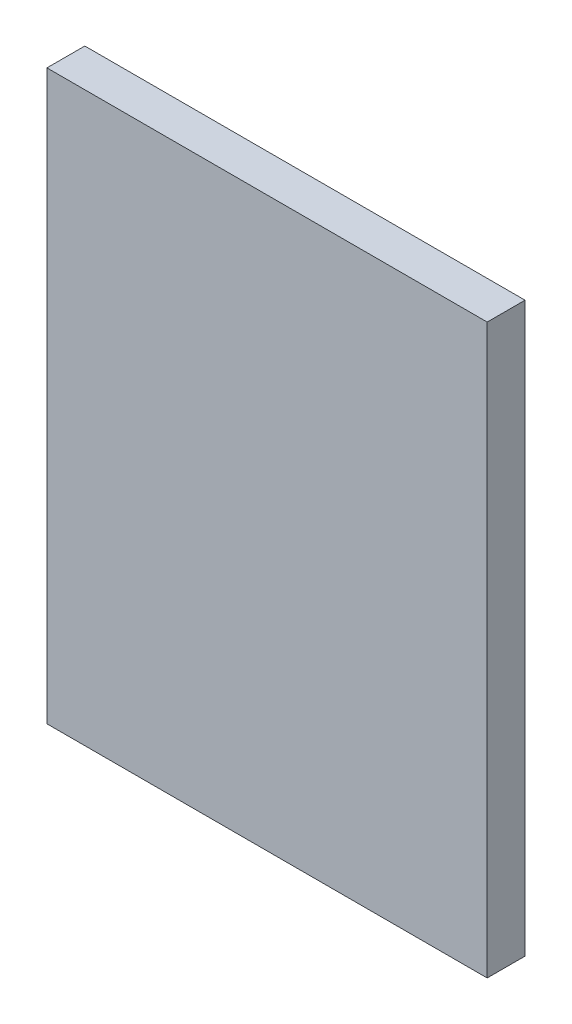
SolidWorks part; units mm, degrees
ref_plane "Plan de face" through (0, 0, 0) normal (0, 0, 1) x (1, 0, 0)
ref_plane "Plan de dessus" through (0, 0, 0) normal (0, 1, 0) x (1, 0, 0)
ref_plane "Plan de droite" through (0, 0, 0) normal (1, 0, 0) x (0, 0, -1)
sketch "Sketch1" plane through (0, 0, 0) normal (0, 0, 1) x (1, 0, 0)
  line L1 (46.5, -60) -> (-46.5, -60)
  line L2 (46.5, -60) -> (46.5, 60)
  line L3 (46.5, 60) -> (-46.5, 60)
  line L4 (-46.5, -60) -> (-46.5, 60)
  line L5 (46.5, -60) -> (-46.5, 60) construction
  line L6 (46.5, 60) -> (-46.5, -60) construction
  point P0 (0, 0)
  dimension "D1" = 93
  dimension "D2" = 120
extrude "Boss-Extrude1" add sketch "Sketch1" along normal blind 8
